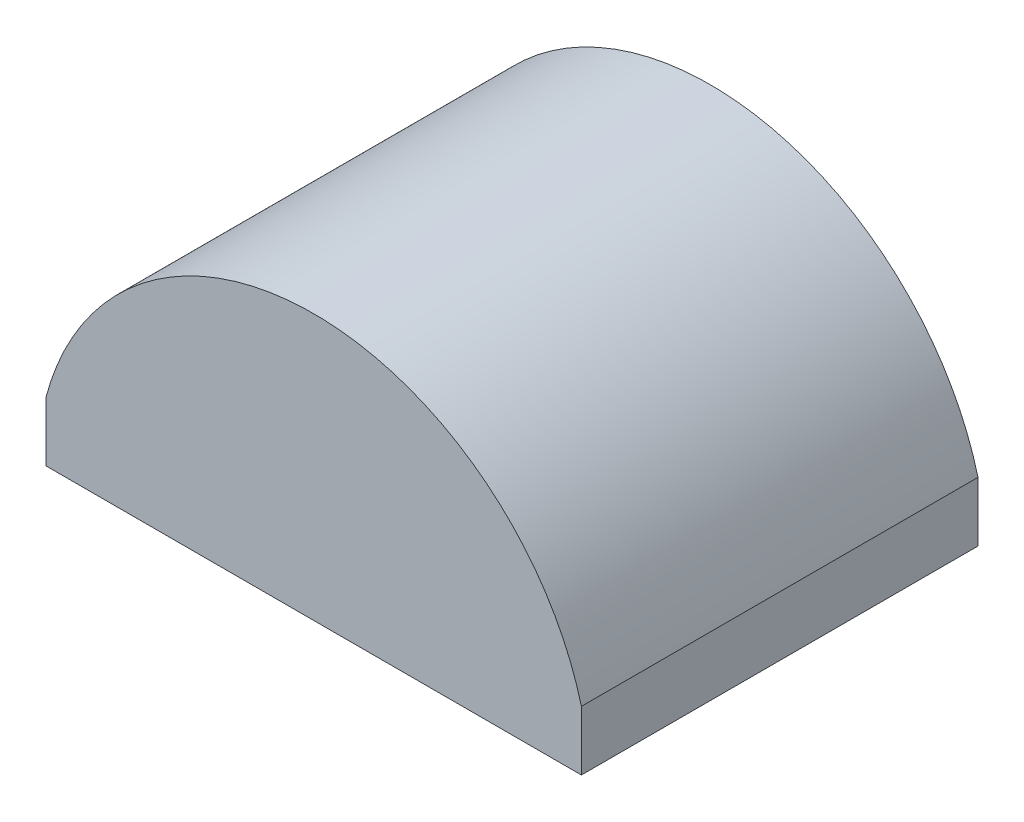
SolidWorks part; units mm, degrees
ref_plane "Front Plane" through (0, 0, 0) normal (0, 0, 1) x (1, 0, 0)
ref_plane "Top Plane" through (0, 0, 0) normal (0, 1, 0) x (1, 0, 0)
ref_plane "Right Plane" through (0, 0, 0) normal (1, 0, 0) x (0, 0, -1)
sketch "Sketch1" plane through (0, 0, 0) normal (0, 0, 1) x (1, 0, 0)
  line L0 (6.75, 2) -> (6.75, 7.2) construction
  line L1 (0, 0) -> (13.5, 0)
  line L2 (0, 0) -> (0, 2)
  line L3 (0, 2) -> (13.5, 2) construction
  line L4 (13.5, 0) -> (13.5, 2)
  arc A0 (0, 2) -> (13.5, 2) centre (6.75, 0.219) cw
  dimension "D1" = 2
  dimension "D2" = 13.5
  dimension "D3" = 5.2
extrude "Boss-Extrude1" add sketch "Sketch1" along normal blind 10
sketch "Sketch2" plane through (0, 0, 0) normal (0, -1, 0) x (1, 0, 0)
  line L0 (0, 10) -> (13.5, 0) construction
  circle A0 centre (6.75, 5) radius 3.6
  dimension "D1" = 7.2
extrude "Cut-Extrude1" cut sketch "Sketch2" against normal blind 4
chamfer "Chamfer1" distance 0.5 angle 45 5 edges at (0, 0, 5) (6.75, 0, 10) (13.5, 0, 5) (6.75, 0, 0) (6.75, 0, 1.4)
